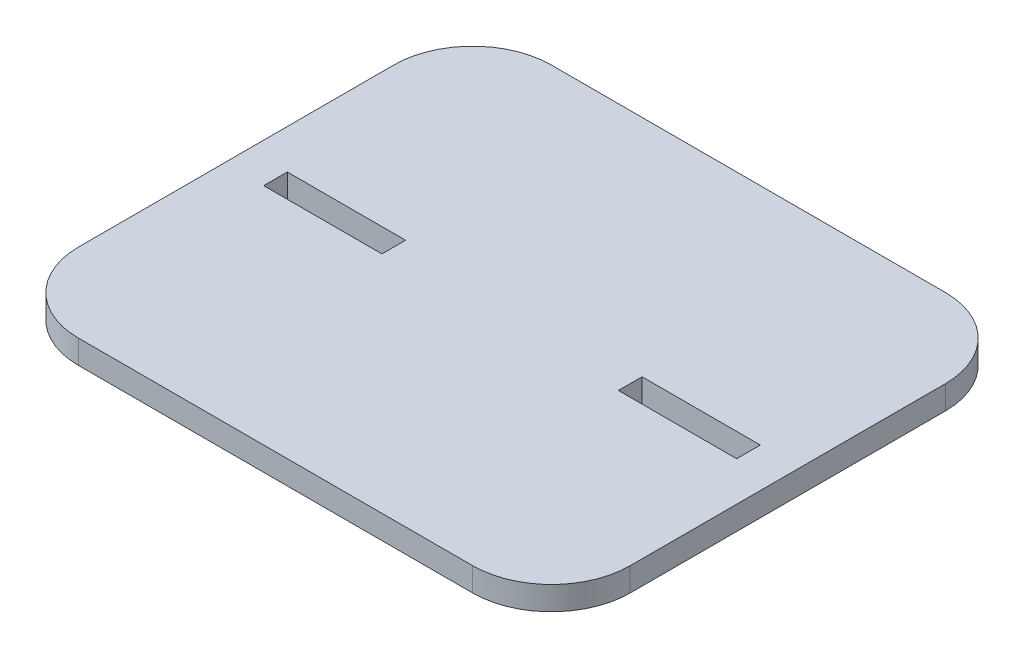
SolidWorks part; units mm, degrees
ref_plane "Front Plane" through (0, 0, 0) normal (0, 0, 1) x (1, 0, 0)
ref_plane "Top Plane" through (0, 0, 0) normal (0, 1, 0) x (1, 0, 0)
ref_plane "Right Plane" through (0, 0, 0) normal (1, 0, 0) x (0, 0, -1)
sketch "Sketch1" plane through (0, 0, 0) normal (0, 1, 0) x (1, 0, 0)
  line L0 (0, 30) -> (71.3409, 30) construction
  line L1 (10, 0) -> (60, 0)
  line L2 (0, 10) -> (0, 50)
  line L3 (10, 60) -> (60, 60)
  line L4 (70, 10) -> (70, 50)
  line L5 (65, 28.5) -> (70, 28.5) construction
  line L6 (5, 31.5) -> (20, 31.5)
  line L7 (5, 31.5) -> (5, 28.5)
  line L8 (5, 28.5) -> (20, 28.5)
  line L9 (20, 31.5) -> (20, 28.5)
  line L10 (5, 31.5) -> (20, 28.5) construction
  line L11 (5, 28.5) -> (20, 31.5) construction
  line L12 (50, 31.5) -> (65, 31.5)
  line L13 (50, 31.5) -> (50, 28.5)
  line L14 (50, 28.5) -> (65, 28.5)
  line L15 (65, 31.5) -> (65, 28.5)
  line L16 (50, 31.5) -> (65, 28.5) construction
  line L17 (50, 28.5) -> (65, 31.5) construction
  line L18 (5, 28.5) -> (0, 28.5) construction
  arc A0 (60, 60) -> (70, 50) centre (60, 50) cw
  arc A1 (0, 50) -> (10, 60) centre (10, 50) cw
  arc A2 (10, 0) -> (0, 10) centre (10, 10) cw
  arc A3 (60, 0) -> (70, 10) centre (60, 10) ccw
  point P7 (70, 60)
  point P10 (0, 60)
  point P13 (0, 0)
  point P18 (12.5, 30)
  point P23 (57.5, 30)
  dimension "D3" = 10
  dimension "D1" = 60
  dimension "D2" = 70
  dimension "D4" = 15
  dimension "D5" = 30
  dimension "D6" = 3
extrude "Boss-Extrude1" add sketch "Sketch1" along normal blind 3
